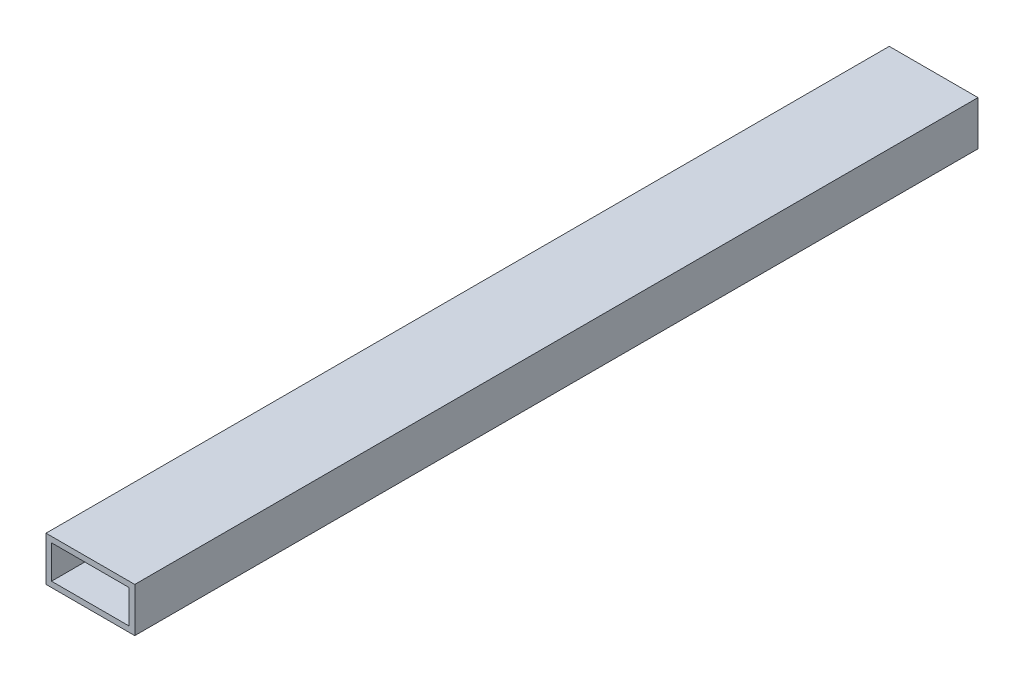
SolidWorks part; units mm, degrees
ref_plane "Front Plane" through (0, 0, 0) normal (0, 0, 1) x (1, 0, 0)
ref_plane "Top Plane" through (0, 0, 0) normal (0, 1, 0) x (1, 0, 0)
ref_plane "Right Plane" through (0, 0, 0) normal (1, 0, 0) x (0, 0, -1)
sketch "Sketch1" plane through (0, 0, 0) normal (0, 0, 1) x (1, 0, 0)
  line L0 (3.175, 22.225) -> (47.625, 22.225)
  line L1 (0, 0) -> (50.8, 0)
  line L2 (0, 0) -> (0, 25.4)
  line L3 (0, 25.4) -> (50.8, 25.4)
  line L4 (50.8, 0) -> (50.8, 25.4)
  line L5 (47.625, 3.175) -> (47.625, 22.225)
  line L6 (3.175, 3.175) -> (47.625, 3.175)
  line L7 (3.175, 3.175) -> (3.175, 22.225)
  dimension "D2" = 50.8
  dimension "D3" = 25.4
  dimension "D1" = 3.175
extrude "Boss-Extrude1" add sketch "Sketch1" along normal blind 482.6
